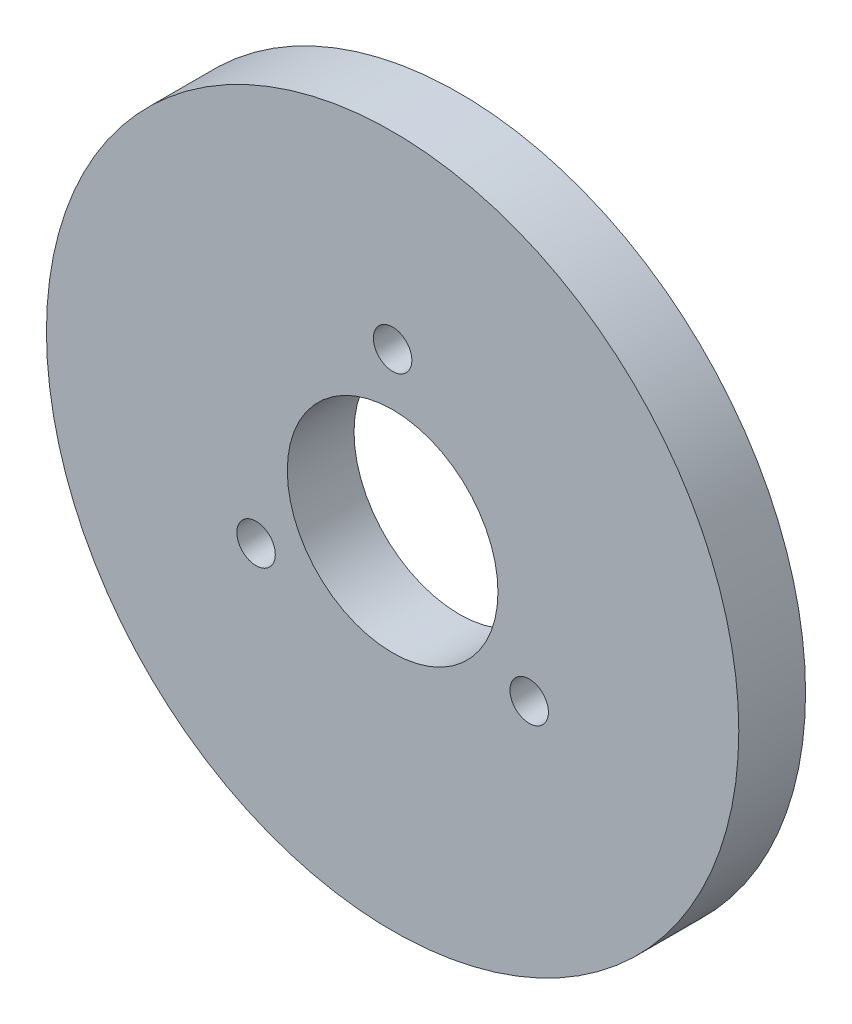
SolidWorks part; units mm, degrees
material "Acrylic (Medium-high impact)"
ref_plane "Front Plane" through (0, 0, 0) normal (0, 0, 1) x (1, 0, 0)
ref_plane "Top Plane" through (0, 0, 0) normal (0, 1, 0) x (1, 0, 0)
ref_plane "Right Plane" through (0, 0, 0) normal (1, 0, 0) x (0, 0, -1)
sketch "Sketch1" plane through (0, 0, 0) normal (0, 0, 1) x (1, 0, 0)
  circle A1 centre (0, 0) radius 10.0203 construction
  circle A2 centre (0, 0) radius 32.9311
  circle A3 centre (0, 0) radius 32.9311
  circle A4 centre (0, 15) radius 1.8288 construction
  circle A5 centre (12.9904, -7.5) radius 1.8288 construction
  circle A6 centre (-12.9904, -7.5) radius 1.8288 construction
  circle A7 centre (0, 0) radius 10.0203
  circle A8 centre (0, 15) radius 1.8288
  circle A9 centre (12.9904, -7.5) radius 1.8288
  circle A10 centre (-12.9904, -7.5) radius 1.8288
  dimension "D1" = 12.7
extrude "Boss-Extrude1" add sketch "Sketch1" along normal blind 6.35
